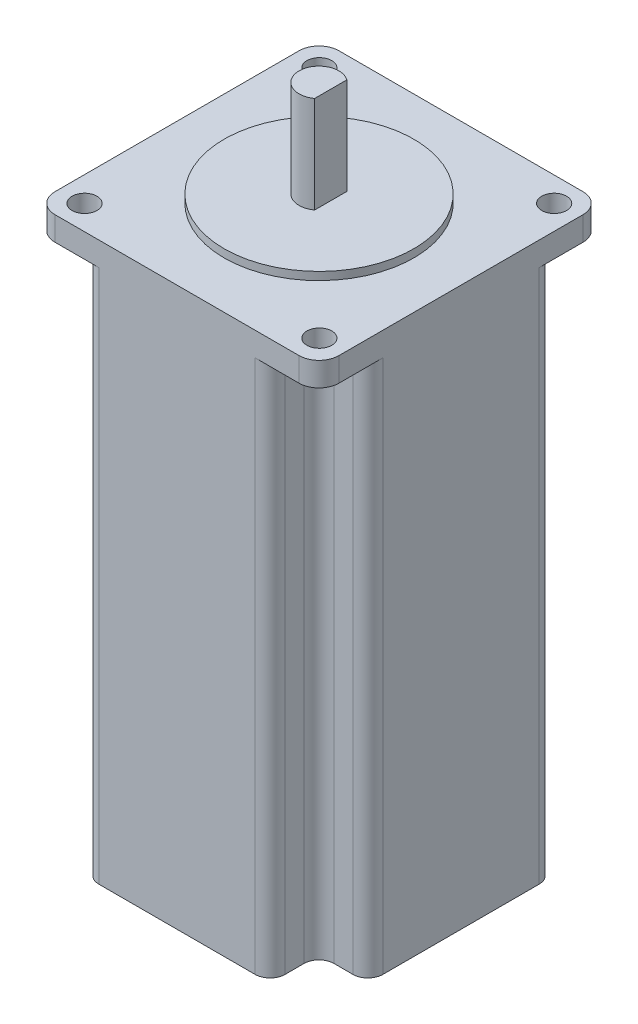
SolidWorks part; units mm, degrees
ref_plane "Front Plane" through (0, 0, 0) normal (0, 0, 1) x (1, 0, 0)
ref_plane "Top Plane" through (0, 0, 0) normal (0, 1, 0) x (1, 0, 0)
ref_plane "Right Plane" through (0, 0, 0) normal (1, 0, 0) x (0, 0, -1)
sketch "Sketch1" plane through (0, 0, 0) normal (0, 1, 0) x (1, 0, 0)
  line L1 (-24.5, -28.5) -> (24.5, -28.5)
  line L2 (-28.5, -24.5) -> (-28.5, 24.5)
  line L3 (-24.5, 28.5) -> (24.5, 28.5)
  line L4 (28.5, -24.5) -> (28.5, 24.5)
  line L5 (-28.5, -28.5) -> (28.5, 28.5) construction
  line L6 (-28.5, 28.5) -> (28.5, -28.5) construction
  arc A0 (-24.5, -28.5) -> (-28.5, -24.5) centre (-24.5, -24.5) cw
  arc A1 (24.5, -28.5) -> (28.5, -24.5) centre (24.5, -24.5) ccw
  arc A2 (24.5, 28.5) -> (28.5, 24.5) centre (24.5, 24.5) cw
  arc A3 (-24.5, 28.5) -> (-28.5, 24.5) centre (-24.5, 24.5) ccw
  point P0 (0, 0)
  dimension "D3" = 4
  dimension "D1" = 57
  dimension "D2" = 57
extrude "Boss-Extrude1" add sketch "Sketch1" along normal blind 112
sketch "Sketch2" plane through (0, 112, 0) normal (0, 1, 0) x (1, 0, 0)
  circle A0 centre (0, 0) radius 19.05
  dimension "D1" = 38.1
extrude "Boss-Extrude2" add sketch "Sketch2" along normal blind 1.6
sketch "Sketch3" plane through (0, 113.6, 0) normal (0, 1, 0) x (1, 0, 0)
  circle A0 centre (0, 0) radius 4
  dimension "D1" = 8
extrude "Boss-Extrude3" add sketch "Sketch3" along normal blind 19.4
sketch "Sketch4" plane through (0, 133, 0) normal (0, 1, 0) x (1, 0, 0)
  line L1 (2.3563, 3.7394) -> (10.2524, 3.7394)
  line L2 (2.3563, 3.7394) -> (2.3563, -3.5855)
  line L3 (2.3563, -3.5855) -> (10.2524, -3.5855)
  line L4 (10.2524, 3.7394) -> (10.2524, -3.5855)
extrude "Cut-Extrude1" cut sketch "Sketch4" against normal blind 19.4 contours L2 L1 L4 L3
sketch "Sketch5" plane through (0, 0, 0) normal (0, -1, 0) x (1, 0, 0)
  line L1 (-28.5, -28.5) -> (28.5, -28.5)
  line L2 (-28.5, -28.5) -> (-28.5, 28.5)
  line L3 (-28.5, 28.5) -> (28.5, 28.5)
  line L4 (28.5, -28.5) -> (28.5, 28.5)
  line L5 (-28.5, -28.5) -> (28.5, 28.5) construction
  line L6 (-28.5, 28.5) -> (28.5, -28.5) construction
  line L7 (-28.5, 28.5) -> (-18.6831, 28.5)
  line L8 (-28.5, 28.5) -> (-28.5, 18.6831)
  line L9 (-28.5, 18.6831) -> (-18.6831, 18.6831)
  line L10 (-18.6831, 28.5) -> (-18.6831, 18.6831)
  line L11 (28.5, 28.5) -> (19.6135, 28.5)
  line L12 (28.5, 28.5) -> (28.5, 19.6135)
  line L13 (28.5, 19.6135) -> (19.6135, 19.6135)
  line L14 (19.6135, 28.5) -> (19.6135, 19.6135)
  line L15 (28.5, -28.5) -> (18.6831, -28.5)
  line L16 (28.5, -28.5) -> (28.5, -18.6831)
  line L17 (28.5, -18.6831) -> (18.6831, -18.6831)
  line L18 (18.6831, -28.5) -> (18.6831, -18.6831)
  line L19 (-28.5, -28.5) -> (-18.6831, -28.5)
  line L20 (-28.5, -28.5) -> (-28.5, -18.6831)
  line L21 (-28.5, -18.6831) -> (-18.6831, -18.6831)
  line L22 (-18.6831, -28.5) -> (-18.6831, -18.6831)
  point P0 (0, 0)
  arc M19 (-24.5, 28.5) -> (-28.5, 24.5) centre (-24.5, 24.5) ccw
  line M20 (-28.5, 24.5) -> (-28.5, -24.5)
extrude "Cut-Extrude2" cut sketch "Sketch5" against normal blind 107.2 contours L10 L3 L9 M19 M20
mirror "Mirror1" about plane through (0, 0, 0) normal (1, 0, 0) of "Cut-Extrude2"
mirror "Mirror2" about plane through (0, 0, 0) normal (0, 0, 1) of "Mirror1", "Cut-Extrude2"
fillet "Fillet1" radius 3 12 edges at (-18.6831, 53.6, -18.6831) (-18.6831, 53.6, 18.6831) (18.6831, 53.6, 18.6831) (28.5, 53.6, -18.6831) (18.6831, 53.6, -18.6831) (18.6831, 53.6, -28.5) (-18.6831, 53.6, -28.5) (-28.5, 53.6, -18.6831) (-18.6831, 53.6, 28.5) (-28.5, 53.6, 18.6831) (28.5, 53.6, 18.6831) (18.6831, 53.6, 28.5)
sketch "Sketch6" plane through (0, 112, 0) normal (0, 1, 0) x (1, 0, 0)
  line L0 (23.5, -23.4298) -> (21, -23.4372) construction
  line L1 (21, -23.4372) -> (-21, -23.5625) construction
  line L2 (-21, -23.5625) -> (-23.5, -23.57) construction
  circle A0 centre (23.64, 23.57) radius 2.5
  circle A1 centre (23.5, -23.4298) radius 2.5
  circle A2 centre (-23.5, 23.57) radius 2.5
  circle A3 centre (-23.5, -23.57) radius 2.5
  point P11 (0, 0)
  point P12 (31.7286, -22.7735)
  point P13 (0, -23.4999)
  dimension "D8" = 5
  dimension "D9" = 5
  dimension "D10" = 5
  dimension "D11" = 5
  dimension "D1" = 47
  dimension "D2" = 23.57
  dimension "D3" = 47.14
  dimension "D4" = 47.14
  dimension "D5" = 47
  dimension "D6" = 23.57
  dimension "D7" = 23.5
extrude "Cut-Extrude3" cut sketch "Sketch6" against normal blind 107.2
